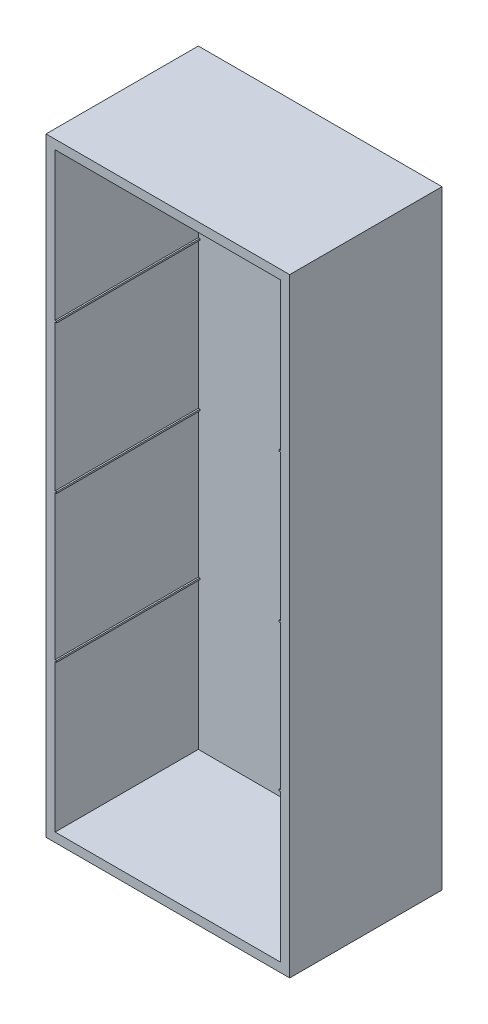
SolidWorks part; units mm, degrees
ref_plane "Front Plane" through (0, 0, 0) normal (0, 0, 1) x (1, 0, 0)
ref_plane "Top Plane" through (0, 0, 0) normal (0, 1, 0) x (1, 0, 0)
ref_plane "Right Plane" through (0, 0, 0) normal (1, 0, 0) x (0, 0, -1)
sketch "Sketch1" plane through (0, 0, 0) normal (0, 0, 1) x (1, 0, 0)
  line L1 (400, -1000) -> (-400, -1000)
  line L2 (400, -1000) -> (400, 1000)
  line L3 (400, 1000) -> (-400, 1000)
  line L4 (-400, -1000) -> (-400, 1000)
  line L5 (400, -1000) -> (-400, 1000) construction
  line L6 (400, 1000) -> (-400, -1000) construction
  point P0 (0, 0)
  dimension "D1" = 2000
  dimension "D2" = 800
extrude "Boss-Extrude1" add sketch "Sketch1" along normal blind 500
shell "Shell2" thickness 30
sketch "Sketch4" plane through (0, 0, 500) normal (0, 0, 1) x (1, 0, 0)
  line L0 (-370, 485) -> (370, 485)
  line L1 (-370, 970) -> (-370, -970) construction
  line L2 (370, -970) -> (370, 970) construction
  line L3 (-370, 0) -> (370, 0)
  line L4 (370, 970) -> (-370, 970) construction
  dimension "D1" = 485
  dimension "D2" = 485
  dimension "D3" = 970
sketch "Sketch6" plane through (370, 0, 0) normal (-1, 0, 0) x (0, 0, 1)
  line L0 (30, -970) -> (30, 970) construction
  line L1 (500, 485) -> (30, 485)
  line L2 (500, 485) -> (500, 480)
  line L3 (500, 480) -> (30, 480)
  line L4 (30, 485) -> (30, 480)
  dimension "D1" = 5
extrude "Boss-Extrude2" add sketch "Sketch6" along normal blind 5
sketch "Sketch8" plane through (-370, 0, 0) normal (1, 0, 0) x (0, 0, -1)
  line L0 (-30, 970) -> (-30, -970) construction
  line L1 (-500, 485) -> (-30, 485)
  line L2 (-500, 485) -> (-500, 480)
  line L3 (-500, 480) -> (-30, 480)
  line L4 (-30, 485) -> (-30, 480)
  dimension "D1" = 5
extrude "Boss-Extrude3" add sketch "Sketch8" along normal blind 5
sketch "Sketch9" plane through (370, 0, 0) normal (-1, 0, 0) x (0, 0, 1)
  line L0 (30, -970) -> (30, 480) construction
  line L1 (500, 0) -> (30, 0)
  line L2 (500, 0) -> (500, -5)
  line L3 (500, -5) -> (30, -5)
  line L4 (30, 0) -> (30, -5)
  dimension "D1" = 5
extrude "Boss-Extrude4" add sketch "Sketch9" along normal blind 5
sketch "Sketch11" plane through (-370, 0, 0) normal (1, 0, 0) x (0, 0, -1)
  line L0 (-30, 480) -> (-30, -970) construction
  line L1 (-500, 0) -> (-30, 0)
  line L2 (-500, 0) -> (-500, -5)
  line L3 (-500, -5) -> (-30, -5)
  line L4 (-30, 0) -> (-30, -5)
  dimension "D1" = 5
extrude "Boss-Extrude5" add sketch "Sketch11" along normal blind 5
sketch "Sketch15" plane through (0, 0, 500) normal (0, 0, 1) x (1, 0, 0)
  line L0 (370, -480) -> (-370, -480)
  line L1 (370, -970) -> (370, -5) construction
  line L2 (-370, -5) -> (-370, -970) construction
  dimension "D1" = 480
sketch "Sketch16" plane through (370, 0, 0) normal (-1, 0, 0) x (0, 0, 1)
  line L0 (30, -970) -> (30, -5) construction
  line L1 (500, -480) -> (30, -480)
  line L2 (500, -480) -> (500, -485)
  line L3 (500, -485) -> (30, -485)
  line L4 (30, -480) -> (30, -485)
  dimension "D1" = 5
extrude "Boss-Extrude6" add sketch "Sketch16" along normal blind 5
sketch "Sketch17" plane through (-370, 0, 0) normal (1, 0, 0) x (0, 0, -1)
  line L0 (-30, -5) -> (-30, -970) construction
  line L1 (-500, -480) -> (-30, -480)
  line L2 (-500, -480) -> (-500, -485)
  line L3 (-500, -485) -> (-30, -485)
  line L4 (-30, -480) -> (-30, -485)
  dimension "D1" = 5
extrude "Boss-Extrude7" add sketch "Sketch17" along normal blind 5
